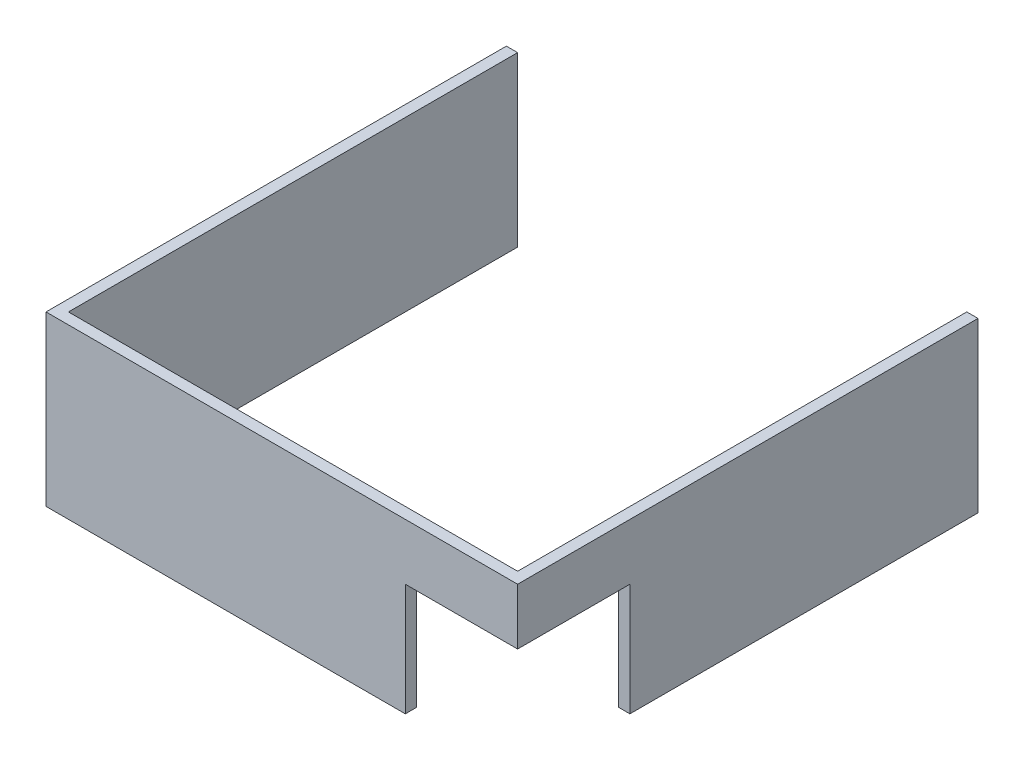
SolidWorks part; units mm, degrees
ref_plane "Front Plane" through (0, 0, 0) normal (0, 0, 1) x (1, 0, 0)
ref_plane "Top Plane" through (0, 0, 0) normal (0, 1, 0) x (1, 0, 0)
ref_plane "Right Plane" through (0, 0, 0) normal (1, 0, 0) x (0, 0, -1)
sketch "Sketch1" plane through (0, 0, 0) normal (0, 1, 0) x (1, 0, 0)
  line L0 (0, 0) -> (80, 0)
  line L1 (0, 0) -> (0, 80)
  line L2 (80, 0) -> (80, 80)
  line L3 (0, 80) -> (-2, 80)
  line L4 (-2, 80) -> (-2, -2)
  line L6 (80, -2) -> (-2, -2)
  line L7 (80, -2) -> (82, -2)
  line L8 (82, -2) -> (82, 80)
  line L9 (82, 80) -> (80, 80)
extrude "Boss-Extrude1" add sketch "Sketch1" along normal blind 30
sketch "Sketch2" plane through (82, 0, 0) normal (1, 0, 0) x (0, 0, -1)
  line L0 (-2, 0) -> (18, 0)
  line L1 (-2, 0) -> (80, 0) construction
  line L2 (-2, 0) -> (-2, 20)
  line L3 (-2, 30) -> (-2, 0) construction
  line L4 (-2, 20) -> (18, 20)
  line L5 (18, 20) -> (18, 0)
extrude "Cut-Extrude1" cut sketch "Sketch2" against normal blind 20
